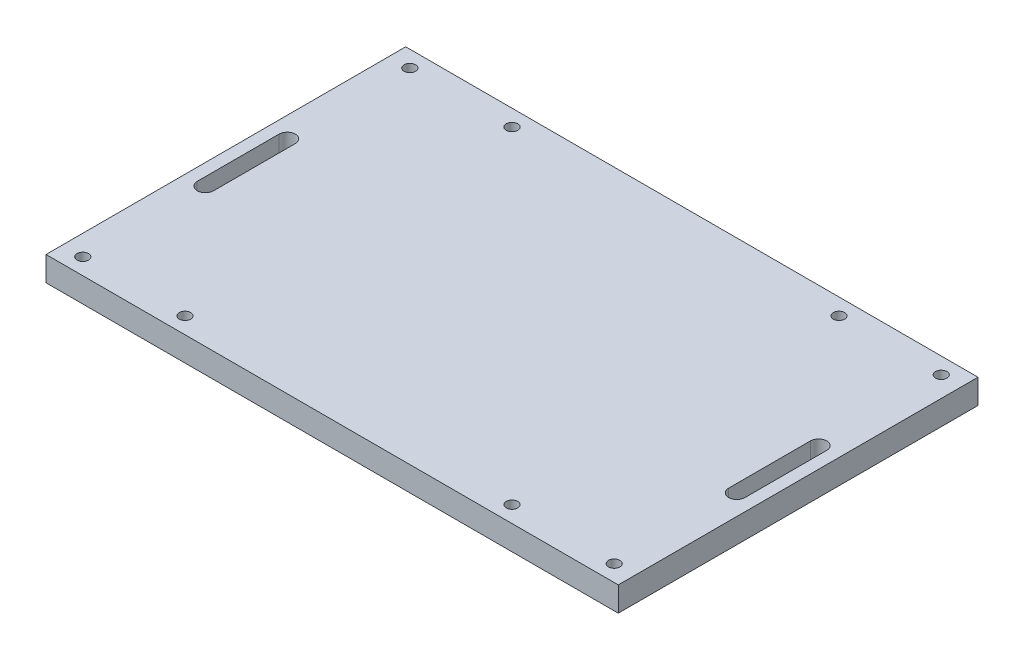
SolidWorks part; units mm, degrees
ref_plane "Front Plane" through (0, 0, 0) normal (0, 0, 1) x (1, 0, 0)
ref_plane "Top Plane" through (0, 0, 0) normal (0, 1, 0) x (1, 0, 0)
ref_plane "Right Plane" through (0, 0, 0) normal (1, 0, 0) x (0, 0, -1)
sketch "Sketch1" plane through (0, 0, 0) normal (0, 1, 0) x (1, 0, 0)
  line L1 (-175, -110) -> (175, -110)
  line L2 (-175, -110) -> (-175, 110)
  line L3 (-175, 110) -> (175, 110)
  line L4 (175, -110) -> (175, 110)
  line L5 (-175, -110) -> (175, 110) construction
  line L6 (-175, 110) -> (175, -110) construction
  point P0 (0, 0)
  dimension "D1" = 350
  dimension "D2" = 220
extrude "Boss-Extrude1" add sketch "Sketch1" along normal mid plane 15
sketch "Sketch2" plane through (0, 7.5, 0) normal (0, 1, 0) x (1, 0, 0)
  line L2 (175, 110) -> (-175, 110) construction
  circle A0 centre (-100, 100) radius 3.5
  dimension "D1" = 100
  dimension "D3" = 7
  dimension "D2" = 10
extrude "Cut-Extrude1" cut sketch "Sketch2" against normal through all both and the other way through all
mirror "Mirror1" about plane through (0, 0, 0) normal (0, 0, 1) of "Cut-Extrude1"
mirror "Mirror2" about plane through (0, 0, 0) normal (1, 0, 0) of "Mirror1", "Cut-Extrude1"
sketch "Sketch3" plane through (0, 7.5, 0) normal (0, 1, 0) x (1, 0, 0)
  line L0 (-162.5, -25) -> (-162.5, 25) construction
  line L1 (-167.5, -25) -> (-167.5, 25)
  line L2 (-157.5, -25) -> (-157.5, 25)
  line L3 (-162.5, -30) -> (-162.5, 30) construction
  line L4 (-175, -110) -> (175, -110) construction
  arc A0 (-167.5, -25) -> (-157.5, -25) centre (-162.5, -25) ccw
  arc A1 (-157.5, 25) -> (-167.5, 25) centre (-162.5, 25) ccw
  point P2 (-162.5, 0)
  dimension "D3" = 50
  dimension "D1" = 10
  dimension "D2" = 162.5
  dimension "D4" = 110
extrude "Cut-Extrude2" cut sketch "Sketch3" against normal through all both and the other way through all
sketch "Sketch4" plane through (0, 7.5, 0) normal (0, 1, 0) x (1, 0, 0)
  line L0 (175, 110) -> (-175, 110) construction
  circle A0 centre (-162.5, 100) radius 3.5
  dimension "D3" = 7
  dimension "D1" = 10
  dimension "D2" = 162.5
extrude "Cut-Extrude5" cut sketch "Sketch4" against normal through all both and the other way through all
mirror "Mirror3" about plane through (0, 0, 0) normal (0, 0, 1) of "Cut-Extrude5"
mirror "Mirror4" about plane through (0, 0, 0) normal (1, 0, 0) of "Mirror3", "Cut-Extrude5"
mirror "Mirror5" about plane through (0, 0, 0) normal (1, 0, 0) of "Cut-Extrude2"
